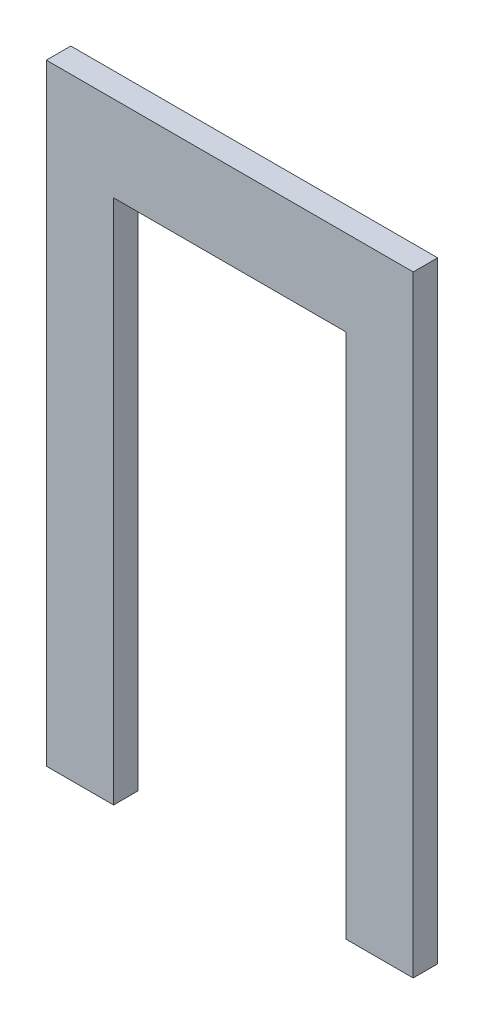
SolidWorks part; units mm, degrees
ref_plane "Alzado" through (0, 0, 0) normal (0, 0, 1) x (1, 0, 0)
ref_plane "Planta" through (0, 0, 0) normal (0, 1, 0) x (1, 0, 0)
ref_plane "Vista lateral" through (0, 0, 0) normal (1, 0, 0) x (0, 0, -1)
sketch "Croquis1" plane through (0, 0, 0) normal (0, 0, 1) x (1, 0, 0)
  line L0 (-475, 900) -> (-475, -1250)
  line L1 (-750, -1250) -> (750, -1250)
  line L2 (-750, -1250) -> (-750, 1250)
  line L3 (-750, 1250) -> (750, 1250)
  line L4 (750, -1250) -> (750, 1250)
  line L5 (-750, -1250) -> (750, 1250) construction
  line L6 (-750, 1250) -> (750, -1250) construction
  line L7 (-475, 900) -> (475, 900)
  line L8 (-475, -1250) -> (475, -1250)
  line L9 (475, 900) -> (475, -1250)
  line L10 (-475, 900) -> (475, -1250) construction
  line L11 (-475, -1250) -> (475, 900) construction
  point P0 (0, 0)
  point P7 (0, -175)
  dimension "D1" = 2500
  dimension "D2" = 1500
  dimension "D3" = 2150
  dimension "D4" = 950
extrude "Saliente-Extruir1" add sketch "Croquis1" along normal blind 100 contours L7 L9 L1 L4 L3 L2 L0
